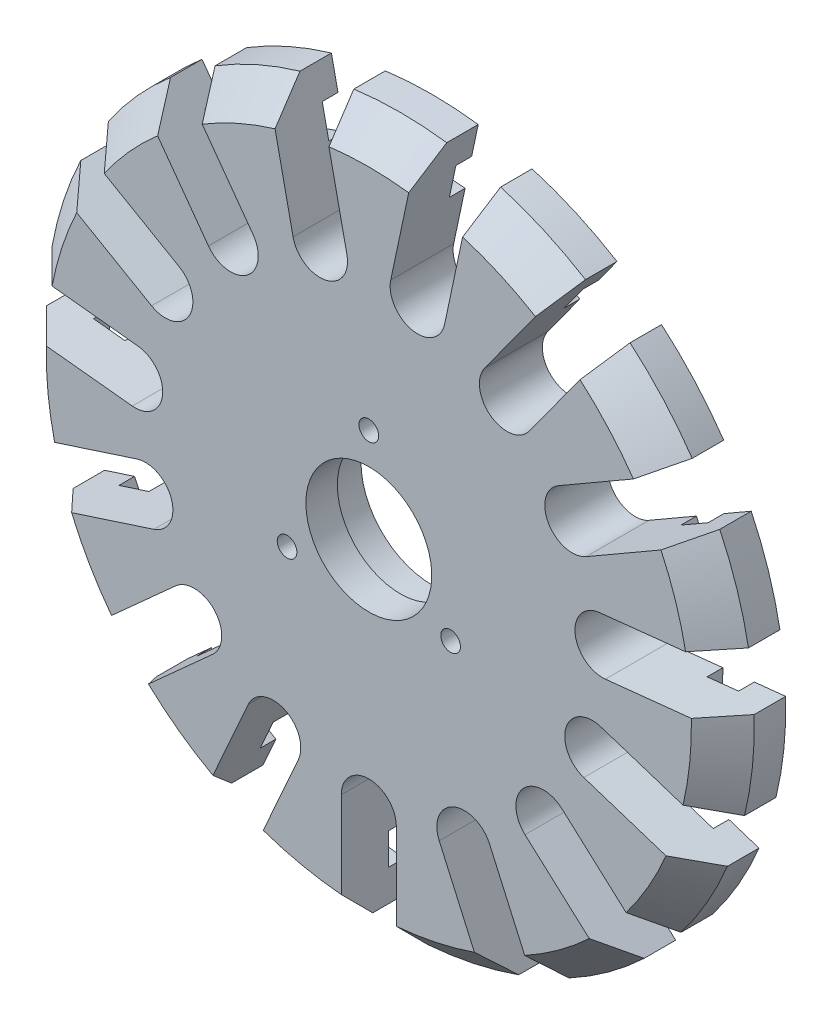
SolidWorks part; units mm, degrees
material "Liga 1060"
ref_plane "Plano frontal" through (0, 0, 0) normal (0, 0, 1) x (1, 0, 0)
ref_plane "Plano superior" through (0, 0, 0) normal (0, 1, 0) x (1, 0, 0)
ref_plane "Plano direito" through (0, 0, 0) normal (1, 0, 0) x (0, 0, -1)
sketch "Esboço1" plane through (0, 0, 0) normal (0, 0, 1) x (1, 0, 0)
  circle A0 centre (0, 0) radius 22.5
  dimension "D1" = 45
extrude "Ressalto-extrusão1" add sketch "Esboço1" along normal blind 4
chamfer "Chanfro1" distance 2 angle 45 1 edges at (22.5, 0, 4)
sketch "Esboço2" plane through (0, 0, 0) normal (0, 0, -1) x (-1, 0, 0)
  line L0 (0, 0) -> (0, 14.4289) construction
  line L1 (1.75, -22.4318) -> (1.75, -14.9318)
  line L2 (-1.75, -22.4318) -> (-1.75, -14.9318)
  arc A0 (-1.75, -22.4318) -> (1.75, -22.4318) centre (0, 0) ccw
  circle A1 centre (0, 0) radius 22.5 construction
  arc A2 (1.75, -14.9318) -> (-1.75, -14.9318) centre (0, -14.9318) ccw
  dimension "D1" = 3.5
  dimension "D2" = 7.5
extrude "Corte-extrusão1" cut sketch "Esboço2" against normal through all
sketch "Esboço3" plane through (0, 0, 0) normal (0, 0, -1) x (-1, 0, 0)
  circle A0 centre (0, 0) radius 4
  dimension "D1" = 8
extrude "Corte-extrusão2" cut sketch "Esboço3" against normal through all
sketch "Esboço4" plane through (0, 0, 0) normal (0, 0, -1) x (-1, 0, 0)
  circle A0 centre (0, 0) radius 4.5
  dimension "D1" = 9
extrude "Corte-extrusão3" cut sketch "Esboço4" against normal blind 2
pattern_circular "PadrãoCircular1" count 15 over 360 about axis through (0, 0, 0) along (0, 0, 1) of "Corte-extrusão1"
sketch "Esboço5" plane through (0, 0, 0) normal (0, 0, -1) x (-1, 0, 0)
  circle A0 centre (0, 0) radius 18.5
  circle A1 centre (0, 0) radius 20.5
  dimension "D1" = 41
  dimension "D2" = 37
extrude "Corte-extrusão4" cut sketch "Esboço5" against normal blind 1
sketch "Esboço9" plane through (0, 0, 0) normal (0, 0, -1) x (-1, 0, 0)
  line L0 (0, 0) -> (0, 6) construction
  dimension "D1" = 6
hole_wizard "Furo roscado de M1.61" positions "3DSketch1" profile "Esboço10" tap size "M1.6" standard "ISO" end condition through all
sketch3d "3DSketch1"
  point P0 (0, 6, 0)
sketch "Esboço10" plane through (0, 6, 0) normal (1, 0, 0) x (0, 1, 0)
  line L0 (0, 0) -> (0, 4)
  line L1 (0, 4) -> (0.625, 4)
  line L2 (0.625, 4) -> (0.625, 0)
  line L5 (0.625, 0) -> (0, 0)
  line L11 (0, -6.35) -> (0, 107.95) construction
  dimension "Thru Tap Drill Dia." = 1.25
  dimension "Thru Tap Drill Depth" = 4
cosmetic thread "Rosca de furo1" parameters "D2"=1.6
pattern_circular "PadrãoCircular2" count 3 over 360 about axis through (0, 0, 0) along (0, 0, 1) of "Furo roscado de M1.61"
cosmetic thread "Rosca de furo2" parameters "D2"=1.6
cosmetic thread "Rosca de furo3" parameters "D2"=1.6
